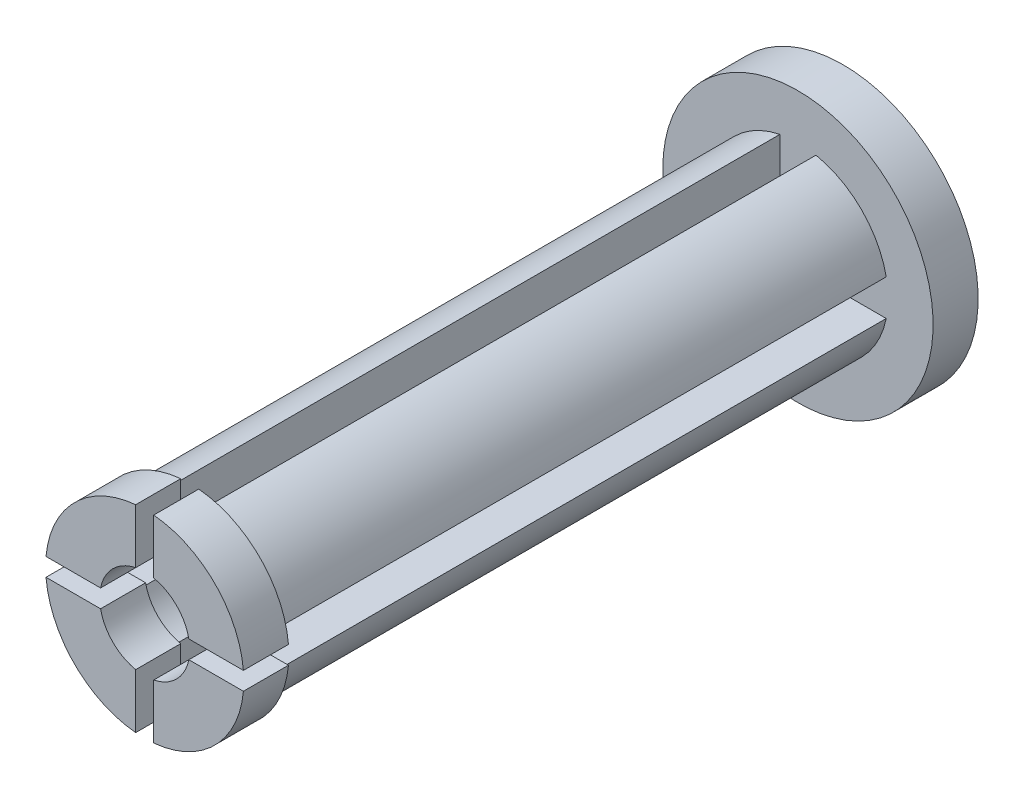
SolidWorks part; units mm, degrees
ref_plane "Front Plane" through (0, 0, 0) normal (0, 0, 1) x (1, 0, 0)
ref_plane "Top Plane" through (0, 0, 0) normal (0, 1, 0) x (1, 0, 0)
ref_plane "Right Plane" through (0, 0, 0) normal (1, 0, 0) x (0, 0, -1)
sketch "Sketch1" plane through (0, 0, 0) normal (0, 0, 1) x (1, 0, 0)
  circle A0 centre (0, 0) radius 2
  dimension "D1" = 4
extrude "Boss-Extrude1" add sketch "Sketch1" along normal blind 13.5
sketch "Sketch2" plane through (0, 0, 13.5) normal (0, 0, 1) x (1, 0, 0)
  circle A0 centre (0, 0) radius 1.2
  dimension "D1" = 2.4
extrude "Cut-Extrude1" cut sketch "Sketch2" against normal through all
sketch "Sketch3" plane through (0, 0, 13.5) normal (0, 0, 1) x (1, 0, 0)
  line L0 (0, -3.2963) -> (0, 3.2963)
  line L1 (-3.5035, 0) -> (3.5035, 0)
  line L2 (0.4, -3.2963) -> (0.4, 3.2963)
  line L3 (-3.5035, -0.4) -> (3.5035, -0.4)
  line L4 (-0.4, -3.2963) -> (-0.4, 3.2963)
  line L5 (-3.5035, 0.4) -> (3.5035, 0.4)
  line L6 (-0.4, 3.2963) -> (0.4, 3.2963)
  line L7 (3.5035, 0.4) -> (3.5035, -0.4)
  line L8 (-3.5035, 0.4) -> (-3.5035, -0.4)
  line L9 (0.4, -3.2963) -> (-0.4, -3.2963)
  circle A2 centre (0, 0) radius 2
  circle A3 centre (0, 0) radius 2
  point P4 (0, 0)
  point P8 (0, 0)
  dimension "D1" = 0
  dimension "D2" = 0.4
  dimension "D3" = 0.4
extrude "Cut-Extrude3" cut sketch "Sketch3" against normal through all contours L8 L2 L3 L0 | L6 L0 L3 L2 | L4 L8 L0 L3 | L4 L5 L0 L8 | L0 L5 L2 L8 | L5 L8 L1 L3 | L8 L3 L1 | L3 L2 L8 L0 | L4 L3 L0 L8 | L3 L8 L1 | L5 L3 L1 L8
sketch "Sketch4" plane through (0, 0, 13.5) normal (0, 0, 1) x (1, 0, 0)
  line L10 (-2.1909, 0.2) -> (-0.9798, 0.2)
  line L11 (-0.2, 0.9798) -> (-0.2, 2.1909)
  line L12 (-2.1909, 0.2) -> (-0.9798, 0.2)
  line L13 (-0.2, 0.9798) -> (-0.2, 2.1909)
  line L16 (0.9798, 0.2) -> (2.1909, 0.2)
  line L17 (0.2, 2.1909) -> (0.2, 0.9798)
  line L18 (0.9798, 0.2) -> (2.1909, 0.2)
  line L19 (0.2, 2.1909) -> (0.2, 0.9798)
  line L24 (0.2, -0.9798) -> (0.2, -2.1909)
  line L25 (2.1909, -0.2) -> (0.9798, -0.2)
  line L26 (0.2, -0.9798) -> (0.2, -2.1909)
  line L27 (2.1909, -0.2) -> (0.9798, -0.2)
  line L30 (-0.9798, -0.2) -> (-2.1909, -0.2)
  line L31 (-0.2, -2.1909) -> (-0.2, -0.9798)
  line L32 (-0.9798, -0.2) -> (-2.1909, -0.2)
  line L33 (-0.2, -2.1909) -> (-0.2, -0.9798)
  arc A10 (-0.2, 2.1909) -> (-2.1909, 0.2) centre (0, 0) ccw
  arc A11 (-0.2, 0.9798) -> (-0.9798, 0.2) centre (0, 0) ccw
  arc A12 (-0.2, 2.1909) -> (-2.1909, 0.2) centre (0, 0) ccw
  arc A13 (-0.2, 0.9798) -> (-0.9798, 0.2) centre (0, 0) ccw
  arc A16 (0.9798, 0.2) -> (0.2, 0.9798) centre (0, 0) ccw
  arc A17 (2.1909, 0.2) -> (0.2, 2.1909) centre (0, 0) ccw
  arc A18 (0.9798, 0.2) -> (0.2, 0.9798) centre (0, 0) ccw
  arc A19 (2.1909, 0.2) -> (0.2, 2.1909) centre (0, 0) ccw
  arc A24 (0.2, -2.1909) -> (2.1909, -0.2) centre (0, 0) ccw
  arc A25 (0.2, -0.9798) -> (0.9798, -0.2) centre (0, 0) ccw
  arc A26 (0.2, -2.1909) -> (2.1909, -0.2) centre (0, 0) ccw
  arc A27 (0.2, -0.9798) -> (0.9798, -0.2) centre (0, 0) ccw
  arc A30 (-2.1909, -0.2) -> (-0.2, -2.1909) centre (0, 0) ccw
  arc A31 (-0.9798, -0.2) -> (-0.2, -0.9798) centre (0, 0) ccw
  arc A32 (-2.1909, -0.2) -> (-0.2, -2.1909) centre (0, 0) ccw
  arc A33 (-0.9798, -0.2) -> (-0.2, -0.9798) centre (0, 0) ccw
  dimension "D1" = 0.2
  dimension "D2" = 0.2
  dimension "D3" = 0.2
  dimension "D4" = 0.2
extrude "Boss-Extrude2" add sketch "Sketch4" along normal blind 1
sketch "Sketch5" plane through (0, 0, 0) normal (0, 0, -1) x (-1, 0, 0)
  circle A0 centre (0, 0) radius 3
  dimension "D1" = 6
extrude "Boss-Extrude3" add sketch "Sketch5" along normal blind 1
